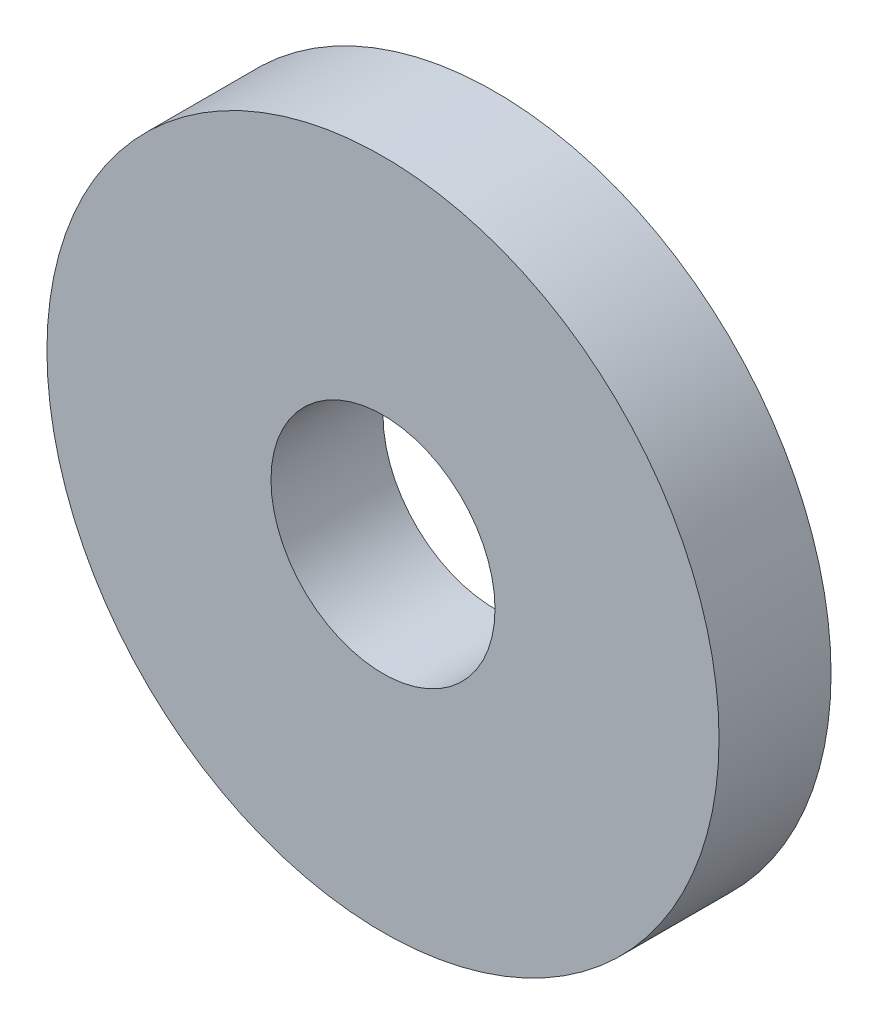
SolidWorks part; units mm, degrees
ref_plane "前视基准面" through (0, 0, 0) normal (0, 0, 1) x (1, 0, 0)
ref_plane "上视基准面" through (0, 0, 0) normal (0, 1, 0) x (1, 0, 0)
ref_plane "右视基准面" through (0, 0, 0) normal (1, 0, 0) x (0, 0, -1)
sketch "草图1" plane through (0, 0, 0) normal (0, 0, 1) x (1, 0, 0)
  circle A1 centre (0, 0) radius 30
extrude "凸台-拉伸1" add sketch "草图1" along normal blind 10
sketch "草图2" plane through (0, 0, 0) normal (0, 0, 1) x (1, 0, 0)
  circle A0 centre (0, 0) radius 20
  circle A1 centre (0, 0) radius 15
extrude "切除-拉伸1" cut sketch "草图2" along normal blind 7 contours A1 | A0
sketch "草图3" plane through (0, 0, 0) normal (0, 0, -1) x (-1, 0, 0)
  circle A0 centre (0, 0) radius 10
extrude "切除-拉伸2" cut sketch "草图3" against normal blind 10
